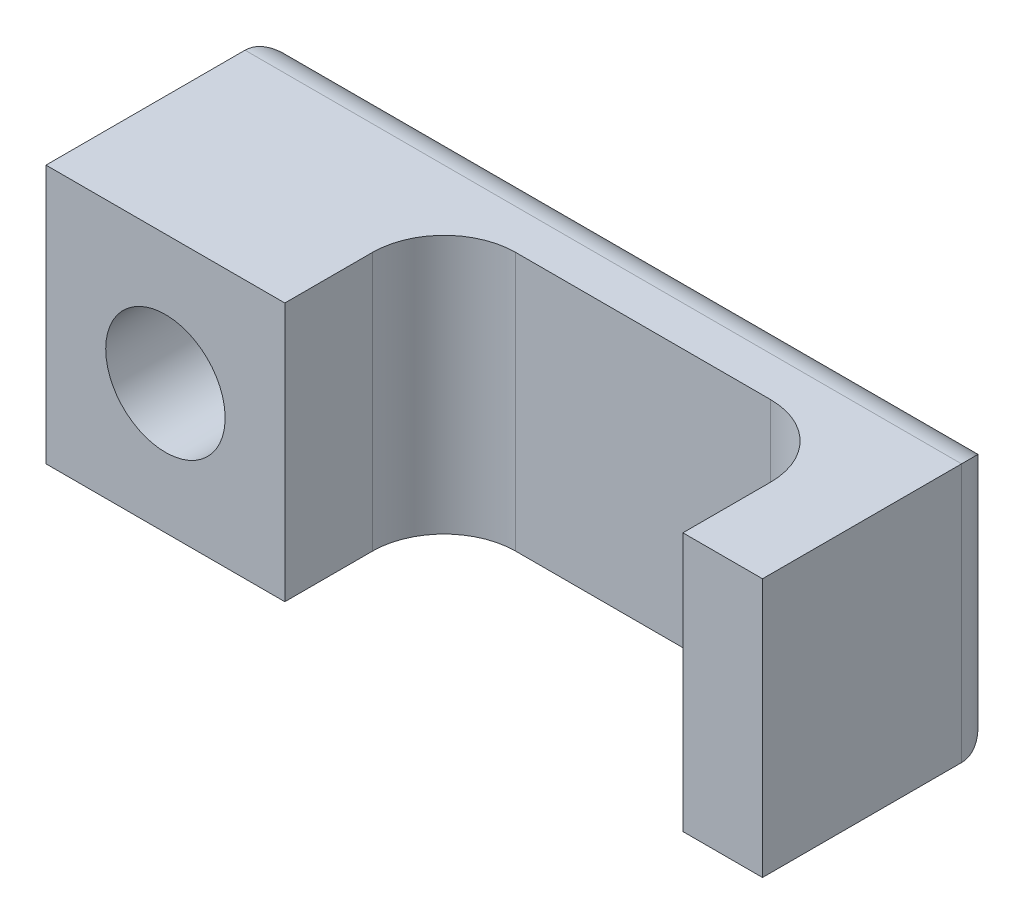
SolidWorks part; units mm, degrees
ref_plane "Front Plane" through (0, 0, 0) normal (0, 0, 1) x (1, 0, 0)
ref_plane "Top Plane" through (0, 0, 0) normal (0, 1, 0) x (1, 0, 0)
ref_plane "Right Plane" through (0, 0, 0) normal (1, 0, 0) x (0, 0, -1)
sketch "Side" plane through (0, 0, 0) normal (0, 1, 0) x (1, 0, 0)
  line L1 (0, 0) -> (18, 0)
  line L2 (0, 0) -> (0, 6)
  line L3 (0, 6) -> (18, 6)
  line L4 (18, 0) -> (18, 6)
  dimension "D1" = 18
  dimension "D2" = 6
extrude "Side_Ex" add sketch "Side" along normal blind 6.5
sketch "Wire" plane through (0, 0, 0) normal (0, 1, 0) x (1, 0, 0)
  line L0 (0, 0) -> (18, 0) construction
  line L1 (14.2, 4) -> (7.8, 4)
  line L2 (16, 2.2) -> (16, 0)
  line L3 (16, 0) -> (6, 0)
  line L4 (6, 2.2) -> (6, 0)
  line L5 (0, 6) -> (0, 0) construction
  line L7 (18, 0) -> (18, 6) construction
  line L8 (18, 6) -> (0, 6) construction
  arc A0 (16, 2.2) -> (14.2, 4) centre (14.2, 2.2) ccw
  arc A1 (6, 2.2) -> (7.8, 4) centre (7.8, 2.2) cw
  dimension "D4" = 1.8
  dimension "D5" = 1.8
  dimension "D1" = 6
  dimension "D2" = 2
  dimension "D3" = 2
ref_plane "Plane1" through (0, 0, -6) normal (0, 0, -1) x (-1, 0, 0)
sketch "Hole" plane through (0, 0, -6) normal (0, 0, -1) x (-1, 0, 0)
  line L0 (0, 6.5) -> (0, 0) construction
  line L1 (-18, 6.5) -> (0, 6.5) construction
  circle A0 centre (-3, 3.25) radius 1.5
  dimension "D1" = 3
  dimension "D3" = 3
  dimension "D2" = 3.25
extrude "Hole_Cut" cut sketch "Hole" against normal through all
extrude "Wire_Cut" cut sketch "Wire" along normal through all
fillet "Fillet1" radius 1 4 edges at (18, 3.25, -6) (9, 6.5, -6) (9, 0, -6) (0, 3.25, -6)
